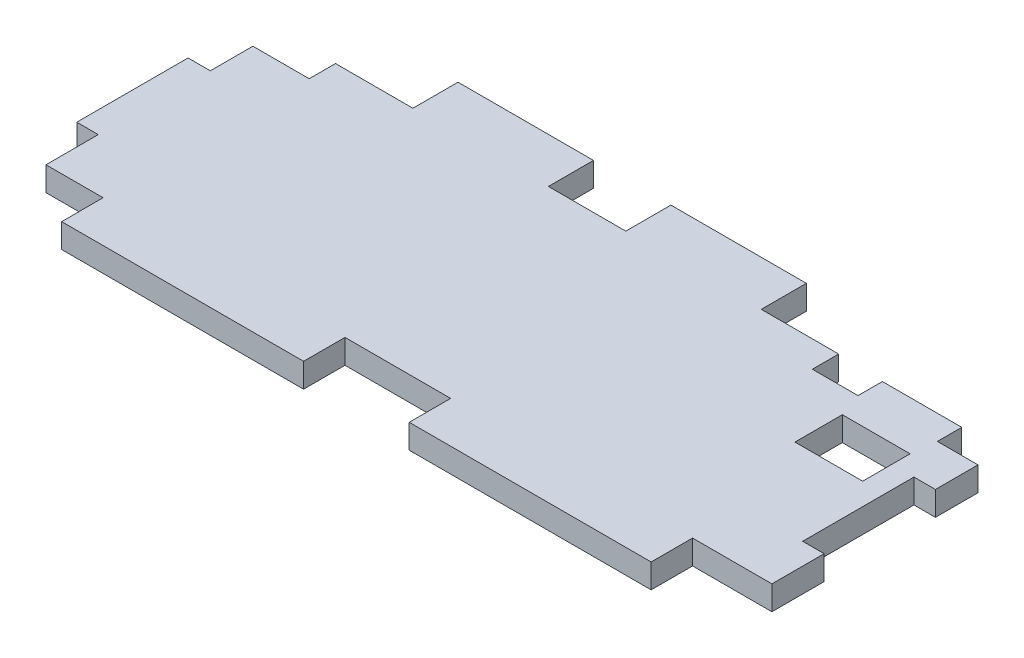
SolidWorks part; units mm, degrees
ref_plane "Front Plane" through (0, 0, 0) normal (0, 0, 1) x (1, 0, 0)
ref_plane "Top Plane" through (0, 0, 0) normal (0, 1, 0) x (1, 0, 0)
ref_plane "Right Plane" through (0, 0, 0) normal (1, 0, 0) x (0, 0, -1)
sketch "Sketch1" plane through (0, 0, 0) normal (0, 1, 0) x (1, 0, 0)
  line L0 (-30.5054, 17.0815) -> (-30.7594, 17.0815)
  line L1 (-30.7594, 17.0815) -> (-30.7594, 22.5171)
  line L2 (25.1206, 14.1605) -> (31.115, 14.1605)
  line L3 (31.115, 14.1605) -> (31.115, 16.9799)
  line L4 (31.115, 16.9799) -> (41.529, 16.9799)
  line L5 (41.529, 16.9799) -> (41.529, 14.1605)
  line L6 (41.529, 14.1605) -> (46.863, 14.1605)
  line L15 (-1000, 0) -> (49000, 0) construction
  line L16 (0, -1000) -> (0, 49000) construction
  line L40 (-51.2318, 7.3025) -> (-51.2318, 0)
  line L41 (-48.3108, 7.3025) -> (-51.2318, 7.3025)
  line L42 (-48.3108, 14.1605) -> (-48.3108, 7.3025)
  line L43 (-40.9194, 14.1605) -> (-48.3108, 14.1605)
  line L44 (-40.9194, 17.0815) -> (-40.9194, 14.1605)
  line L45 (-30.5054, 17.0815) -> (-40.9194, 17.0815)
  line L50 (44.0436, -7.3025) -> (46.863, -7.3025)
  line L51 (46.863, -7.3025) -> (46.863, -14.1605)
  line L52 (46.863, -14.1605) -> (36.449, -14.1605)
  line L53 (36.449, -14.1605) -> (36.449, -19.5961)
  line L54 (36.449, -19.5961) -> (4.699, -19.5961)
  line L55 (4.699, -19.5961) -> (4.699, -14.1605)
  line L56 (4.699, -14.1605) -> (-9.1694, -14.1605)
  line L57 (-9.1694, -19.5961) -> (-40.9194, -19.5961)
  line L58 (-40.9194, -14.1605) -> (-48.4124, -14.1605)
  line L59 (-48.4124, -14.1605) -> (-48.4124, -7.3025)
  line L60 (-48.4124, -7.3025) -> (-51.2318, -7.3025)
  line L61 (-9.1694, -14.1605) -> (-9.1694, -19.5961)
  line L62 (-40.9194, -19.5961) -> (-40.9194, -14.1605)
  line L64 (-12.9794, 22.5171) -> (-30.7594, 22.5171)
  line L65 (-12.9794, 17.0815) -> (-12.9794, 22.5171)
  line L66 (-2.8194, 17.0815) -> (-12.9794, 17.0815)
  line L67 (-2.8194, 22.5171) -> (-2.8194, 17.0815)
  line L68 (14.9606, 22.5171) -> (-2.8194, 22.5171)
  line L69 (14.9606, 17.0815) -> (14.9606, 22.5171)
  line L70 (25.1206, 17.0815) -> (14.9606, 17.0815)
  line L71 (25.1206, 14.1605) -> (25.1206, 17.0815)
  line L73 (46.863, 7.3025) -> (46.863, 14.1605)
  line L74 (44.0436, 7.3025) -> (46.863, 7.3025)
  line L75 (44.0436, 0) -> (44.0436, 7.3025)
  line L76 (-51.2318, -7.3025) -> (-51.2318, 0)
  line L77 (44.0436, -7.3025) -> (44.0436, 0)
  dimension "D1" = 10.16
  dimension "D2" = 7.3914
  dimension "D3" = 14.605
  dimension "D4" = 10.16
  dimension "D5" = 2.921
  dimension "D6" = 5.9944
  dimension "D7" = 2.8194
  dimension "D8" = 10.414
  dimension "D10" = 10.16
  dimension "D11" = 2.921
  dimension "D12" = 17.78
  dimension "D13" = 17.78
  dimension "D14" = 5.334
  dimension "D15" = 7.3025
  dimension "D16" = 6.858
  dimension "D17" = 2.921
  dimension "D18" = 5.4356
  dimension "D19" = 5.4356
  dimension "D20" = 2.8194
  dimension "D21" = 7.493
  dimension "D22" = 31.75
  dimension "D23" = 13.8684
  dimension "D24" = 31.75
  dimension "D25" = 10.414
  dimension "D26" = 5.4356
  dimension "D27" = 5.4356
  dimension "D28" = 5.4356
extrude "Boss-Extrude2" add sketch "Sketch1" along normal mid plane 3.175
sketch "Sketch2" plane through (0, 1.5875, 0) normal (0, 1, 0) x (1, 0, 0)
  line L0 (46.863, 7.3025) -> (46.863, 14.1605) construction
  line L1 (31.242, 10.5791) -> (43.942, 10.5791) construction
  line L2 (31.242, 10.5791) -> (31.242, 2.9591) construction
  line L3 (31.242, 2.9591) -> (43.942, 2.9591) construction
  line L4 (43.942, 10.5791) -> (43.942, 2.9591) construction
  line L5 (41.529, 14.1605) -> (46.863, 14.1605) construction
  line L7 (32.258, 9.6901) -> (41.148, 9.6901)
  line L8 (32.258, 9.6901) -> (32.258, 3.4671)
  line L9 (32.258, 3.4671) -> (41.148, 3.4671)
  line L10 (41.148, 9.6901) -> (41.148, 3.4671)
  dimension "D1" = 12.7
  dimension "D2" = 7.62
  dimension "D3" = 2.921
  dimension "D4" = 3.5814
  dimension "D5" = 8.89
  dimension "D6" = 6.223
  dimension "D7" = 1.016
  dimension "D8" = 0.508
extrude "Cut-Extrude1" cut sketch "Sketch2" against normal blind 3.175
sketch "Sketch4" plane through (0, 1.5875, 0) normal (0, 1, 0) x (1, 0, 0)
  line L0 (-48.3108, 14.1605) -> (-48.3108, 7.3025) construction
  line L1 (-40.9194, 14.1605) -> (-48.3108, 14.1605)
  line L2 (-40.9194, 14.1605) -> (-40.9194, 12.8905)
  line L3 (-40.9194, 12.8905) -> (-48.3108, 12.8905)
  line L4 (-48.3108, 14.1605) -> (-48.3108, 12.8905)
  line L5 (25.1206, 14.1605) -> (25.1206, 17.0815) construction
  line L6 (31.115, 14.1605) -> (25.1206, 14.1605)
  line L7 (31.115, 14.1605) -> (31.115, 12.8905)
  line L8 (31.115, 12.8905) -> (25.1206, 12.8905)
  line L9 (25.1206, 14.1605) -> (25.1206, 12.8905)
  line L10 (46.863, 14.1605) -> (41.529, 14.1605)
  line L11 (46.863, 14.1605) -> (46.863, 12.8905)
  line L12 (46.863, 12.8905) -> (41.529, 12.8905)
  line L13 (41.529, 14.1605) -> (41.529, 12.8905)
  line L14 (41.529, 16.9799) -> (41.529, 14.1605) construction
  dimension "D1" = 1.27
extrude "Cut-Extrude2" cut sketch "Sketch4" against normal through all
sketch "Sketch5" plane through (0, -1.5875, 0) normal (0, -1, 0) x (1, 0, 0)
  line L0 (31.115, -12.8905) -> (31.115, -16.9799) construction
  line L1 (41.529, -16.9799) -> (31.115, -16.9799)
  line L2 (41.529, -16.9799) -> (41.529, -16.3449)
  line L3 (41.529, -16.3449) -> (31.115, -16.3449)
  line L4 (31.115, -16.9799) -> (31.115, -16.3449)
  line L5 (-40.9194, -17.0815) -> (-40.9194, -12.8905) construction
  line L6 (25.1206, -17.0815) -> (14.9606, -17.0815)
  line L7 (25.1206, -17.0815) -> (25.1206, -16.3449)
  line L8 (25.1206, -16.3449) -> (14.9606, -16.3449)
  line L9 (14.9606, -17.0815) -> (14.9606, -16.3449)
  line L10 (-2.8194, -17.0815) -> (-12.9794, -17.0815)
  line L11 (-2.8194, -17.0815) -> (-2.8194, -16.3449)
  line L12 (-2.8194, -16.3449) -> (-12.9794, -16.3449)
  line L13 (-12.9794, -17.0815) -> (-12.9794, -16.3449)
  line L14 (-30.7594, -17.0815) -> (-40.9194, -17.0815)
  line L15 (-30.7594, -17.0815) -> (-30.7594, -16.3449)
  line L16 (-30.7594, -16.3449) -> (-40.9194, -16.3449)
  line L17 (-40.9194, -17.0815) -> (-40.9194, -16.3449)
  line L18 (14.9606, -17.0815) -> (14.9606, -22.5171) construction
  line L19 (-12.9794, -17.0815) -> (-12.9794, -22.5171) construction
  dimension "D1" = 0.635
extrude "Cut-Extrude3" cut sketch "Sketch5" against normal through all
sketch "Sketch6" plane through (0, -1.5875, 0) normal (0, -1, 0) x (1, 0, 0)
  line L0 (-2.8194, -22.5171) -> (-2.8194, -16.3449) construction
  line L1 (14.9606, -22.5171) -> (-2.8194, -22.5171)
  line L2 (14.9606, -22.5171) -> (14.9606, -22.2631)
  line L3 (14.9606, -22.2631) -> (-2.8194, -22.2631)
  line L4 (-2.8194, -22.5171) -> (-2.8194, -22.2631)
  line L5 (-30.7594, -16.3449) -> (-30.7594, -22.5171) construction
  line L6 (-12.9794, -22.5171) -> (-30.7594, -22.5171)
  line L7 (-12.9794, -22.5171) -> (-12.9794, -22.2631)
  line L8 (-12.9794, -22.2631) -> (-30.7594, -22.2631)
  line L9 (-30.7594, -22.5171) -> (-30.7594, -22.2631)
  dimension "D1" = 0.254
extrude "Cut-Extrude4" cut sketch "Sketch6" against normal through all
sketch "Sketch7" plane through (0, -1.5875, 0) normal (0, -1, 0) x (1, 0, 0)
  line L0 (31.115, -12.8905) -> (31.115, -16.3449) construction
  line L1 (41.529, -16.3449) -> (31.115, -16.3449)
  line L2 (41.529, -16.3449) -> (41.529, -16.0909)
  line L3 (41.529, -16.0909) -> (31.115, -16.0909)
  line L4 (31.115, -16.3449) -> (31.115, -16.0909)
  dimension "D1" = 0.254
extrude "Cut-Extrude5" cut sketch "Sketch7" against normal through all
